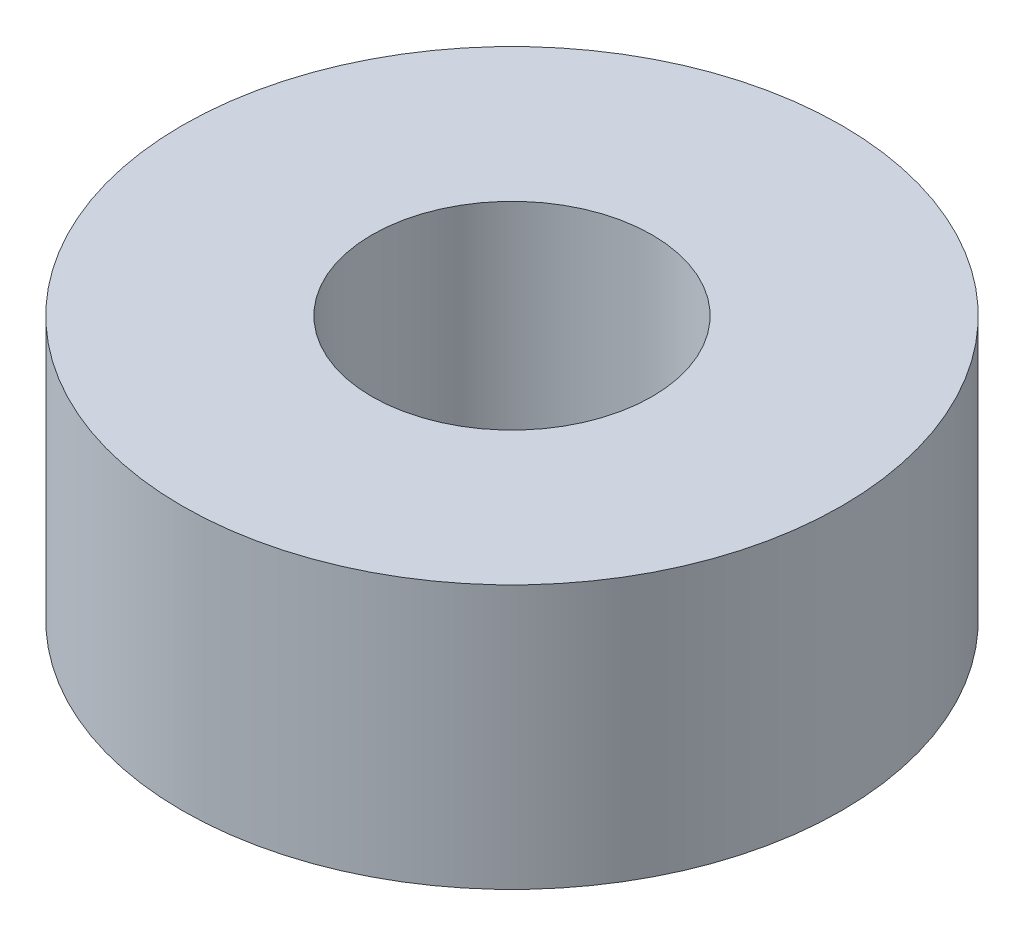
SolidWorks part; units mm, degrees
material "Aleación 6061"
ref_plane "Alzado" through (0, 0, 0) normal (0, 0, 1) x (1, 0, 0)
ref_plane "Planta" through (0, 0, 0) normal (0, 1, 0) x (1, 0, 0)
ref_plane "Vista lateral" through (0, 0, 0) normal (1, 0, 0) x (0, 0, -1)
sketch "Croquis1" plane through (0, 0, 0) normal (0, 1, 0) x (1, 0, 0)
  circle A0 centre (0, -171.45) radius 10
  dimension "D1" = 20
  dimension "D2" = 171.45
extrude "Buje_D20" add sketch "Croquis1" along normal blind 8 from offset 4
sketch "Croquis2" plane through (0, 0, 0) normal (0, 1, 0) x (1, 0, 0)
  circle A0 centre (0, -171.45) radius 4.25
  dimension "D1" = 8.5
  dimension "D2" = 171.45
extrude "Rosca_M10" cut sketch "Croquis2" along normal blind 8 from offset 4
